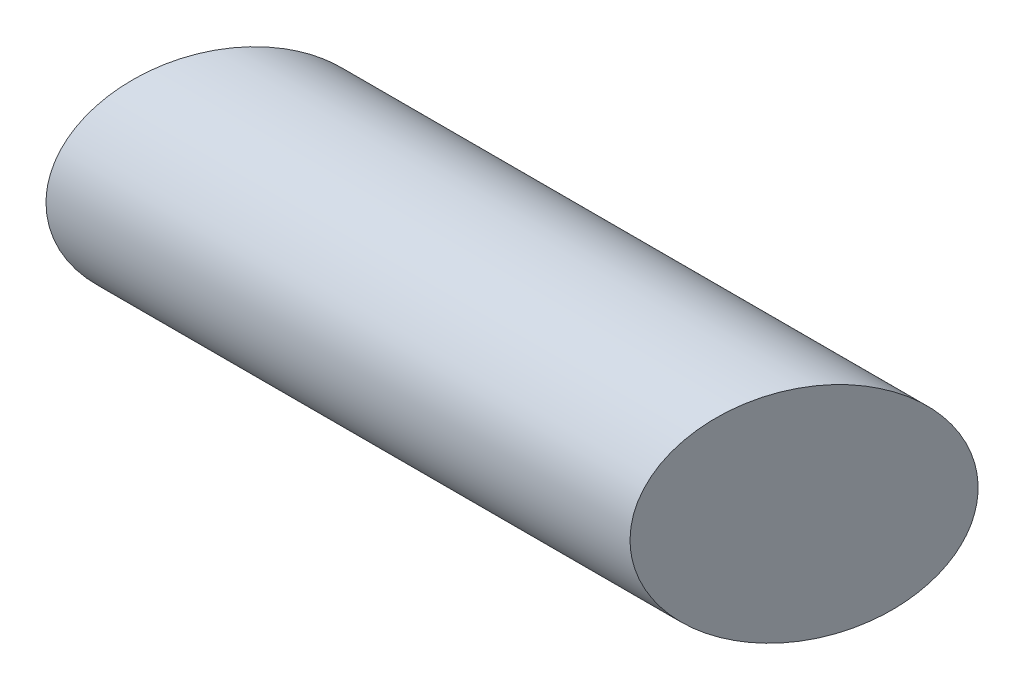
SolidWorks part; units mm, degrees
ref_plane "Front Plane" through (0, 0, 0) normal (0, 0, 1) x (1, 0, 0)
ref_plane "Top Plane" through (0, 0, 0) normal (0, 1, 0) x (1, 0, 0)
ref_plane "Right Plane" through (0, 0, 0) normal (1, 0, 0) x (0, 0, -1)
sketch "Sketch1" plane through (0, 0, 0) normal (1, 0, 0) x (0, 0, -1)
  circle A0 centre (0, 0) radius 6.35
extrude "Boss-Extrude1" add sketch "Sketch1" along normal blind 51.308
sketch "Sketch2" plane through (0, 0, 0) normal (0, 1, 0) x (1, 0, 0)
  line L0 (0, -6.35) -> (7.3323, 6.35)
  line L1 (51.308, 6.35) -> (0, 6.35) construction
  line L2 (7.3323, 6.35) -> (0, 6.35)
  line L3 (0, 6.35) -> (0, -6.35)
  line L4 (51.308, 6.35) -> (0, 6.35) construction
extrude "Cut-Extrude1" cut sketch "Sketch2" against normal through all and the other way through all
sketch "Sketch3" plane through (0, 0, 0) normal (0, 1, 0) x (1, 0, 0)
  line L1 (33.7988, -6.35) -> (41.2432, 6.35)
  line L2 (0, -6.35) -> (51.308, -6.35) construction
  line L3 (51.308, 6.35) -> (7.3323, 6.35) construction
  line L4 (41.2432, 6.35) -> (51.308, 6.35)
  line L5 (51.308, 6.35) -> (51.308, -6.35)
  line L6 (51.308, -6.35) -> (33.7988, -6.35)
extrude "Cut-Extrude2" cut sketch "Sketch3" against normal through all and the other way through all
